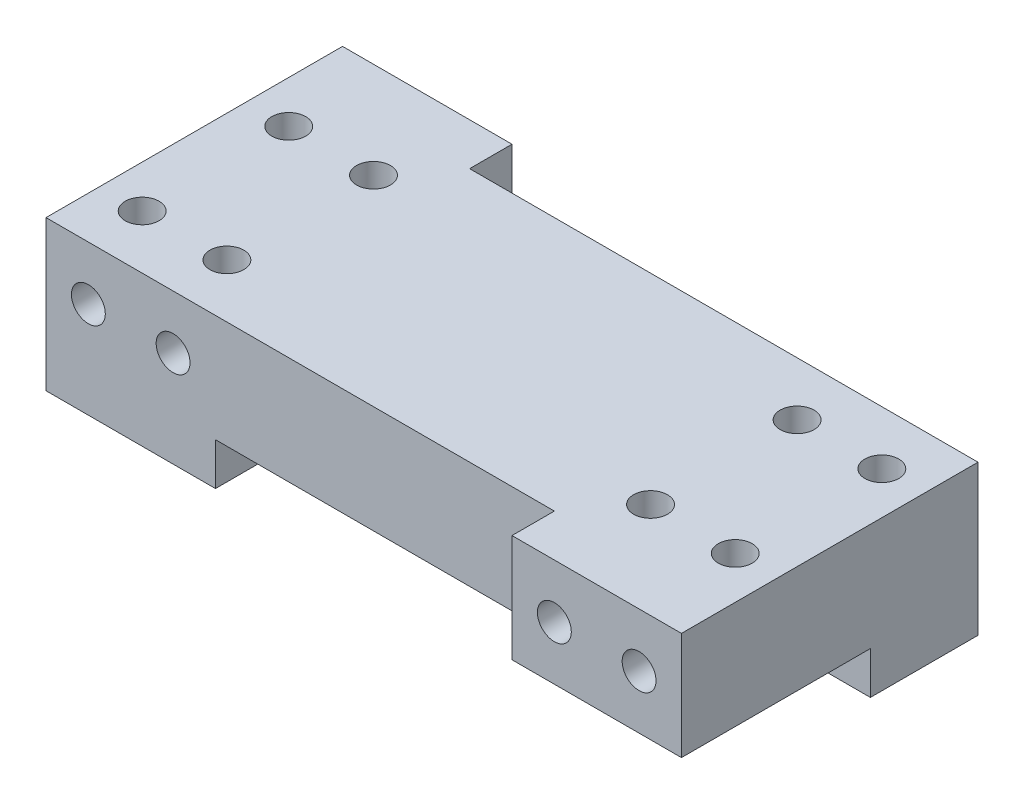
SolidWorks part; units mm, degrees
ref_plane "Front Plane" through (0, 0, 0) normal (0, 0, 1) x (1, 0, 0)
ref_plane "Top Plane" through (0, 0, 0) normal (0, 1, 0) x (1, 0, 0)
ref_plane "Right Plane" through (0, 0, 0) normal (1, 0, 0) x (0, 0, -1)
sketch "Sketch1" plane through (0, 0, 0) normal (0, 1, 0) x (1, 0, 0)
  line L1 (0, 0) -> (-80, 0)
  line L2 (0, 0) -> (0, 80)
  line L3 (0, 80) -> (-80, 80)
  line L4 (-80, 0) -> (-80, 80)
  dimension "D1" = 80
  dimension "D2" = 80
extrude "Boss-Extrude1" add sketch "Sketch1" along normal blind 12.7
sketch "Sketch2" plane through (0, 0, 0) normal (0, 0, 1) x (1, 0, 0)
  line L0 (-80, 12.7) -> (0, 12.7) construction
  line L1 (-80, 12.7) -> (-80, 0) construction
  circle A0 centre (-75, 6.35) radius 2
  circle A1 centre (-65, 6.35) radius 2
  circle A2 centre (-15, 6.35) radius 2
  circle A3 centre (-5, 6.35) radius 2
  dimension "D2" = 4
  dimension "D3" = 4
  dimension "D4" = 4
  dimension "D5" = 4
  dimension "D1" = 6.35
  dimension "D6" = 10
  dimension "D7" = 10
  dimension "D8" = 60
  dimension "D9" = 5
extrude "Cut-Extrude1" cut sketch "Sketch2" against normal through all
sketch "Sketch3" plane through (0, 0, 0) normal (0, 0, 1) x (1, 0, 0)
  line L0 (-80, 0) -> (0, 0) construction
  line L1 (-80, 12.7) -> (-20, 12.7)
  line L2 (-80, 12.7) -> (-80, 0)
  line L3 (-80, 0) -> (-20, 0)
  line L4 (-20, 12.7) -> (-20, 0)
  dimension "D1" = 60
extrude "Cut-Extrude2" cut sketch "Sketch3" against normal blind 25
sketch "Sketch4" plane through (0, 0, -80) normal (0, 0, -1) x (-1, 0, 0)
  line L0 (0, 0) -> (80, 0) construction
  line L1 (0, 12.7) -> (60, 12.7)
  line L2 (0, 12.7) -> (0, 0)
  line L3 (0, 0) -> (60, 0)
  line L4 (60, 12.7) -> (60, 0)
  dimension "D1" = 60
extrude "Cut-Extrude3" cut sketch "Sketch4" against normal blind 25
sketch "Sketch5" plane through (0, 12.7, 0) normal (0, 1, 0) x (1, 0, 0)
  line L0 (-80, 80) -> (-80, 25) construction
  line L1 (0, 0) -> (-80, 80)
  line L2 (-60, 80) -> (-80, 80) construction
  line L3 (-40, 40) -> (-80, 40)
  line L4 (-40, 40) -> (-40, 25)
  line L5 (-20, 25) -> (-80, 25) construction
  circle A0 centre (-75, 48.65) radius 2
  circle A1 centre (-65, 48.65) radius 2
  circle A2 centre (-65, 31.35) radius 2
  circle A3 centre (-75, 31.35) radius 2
  circle A4 centre (-5, 31.35) radius 2
  circle A5 centre (-15, 31.35) radius 2
  circle A6 centre (-5, 48.65) radius 2
  circle A7 centre (-15, 48.65) radius 2
  dimension "D1" = 4
  dimension "D4" = 4
  dimension "D2" = 5
  dimension "D3" = 31.35
  dimension "D5" = 31.35
  dimension "D6" = 10
extrude "Cut-Extrude4" cut sketch "Sketch5" against normal through all contours A0 | A1 | A3 | A2 | A7 | A6 | A4 | A5
sketch "Sketch6" plane through (0, 0, 0) normal (0, 0, 1) x (1, 0, 0)
  line L1 (-20, 12.7) -> (0, 12.7)
  line L2 (-20, 12.7) -> (-20, 0)
  line L3 (-20, 0) -> (0, 0)
  line L4 (0, 12.7) -> (0, 0)
extrude "Cut-Extrude5" cut sketch "Sketch6" against normal blind 20
sketch "Sketch8" plane through (0, 0, -80) normal (0, 0, -1) x (-1, 0, 0)
  line L1 (60, 0) -> (80, 0)
  line L2 (60, 0) -> (60, 12.7)
  line L3 (60, 12.7) -> (80, 12.7)
  line L4 (80, 0) -> (80, 12.7)
extrude "Cut-Extrude6" cut sketch "Sketch8" against normal blind 20
sketch "Sketch9" plane through (0, 0, 0) normal (0, -1, 0) x (1, 0, 0)
  line L1 (0, -55) -> (-20, -55)
  line L2 (0, -55) -> (0, -42.3)
  line L3 (0, -42.3) -> (-20, -42.3)
  line L4 (-20, -55) -> (-20, -42.3)
  line L5 (-80, -25) -> (-60, -25)
  line L6 (-80, -25) -> (-80, -37.7)
  line L7 (-80, -37.7) -> (-60, -37.7)
  line L8 (-60, -25) -> (-60, -37.7)
  circle A0 centre (-65, -31.35) radius 2
  circle A1 centre (-75, -31.35) radius 2
  circle A2 centre (-15, -48.65) radius 2
  circle A3 centre (-5, -48.65) radius 2
  dimension "D6" = 4
  dimension "D7" = 4
  dimension "D8" = 4
  dimension "D9" = 4
  dimension "D1" = 12.7
  dimension "D2" = 20
  dimension "D3" = 20
  dimension "D4" = 12.7
  dimension "D5" = 10
extrude "Boss-Extrude3" add sketch "Sketch9" along normal blind 5
